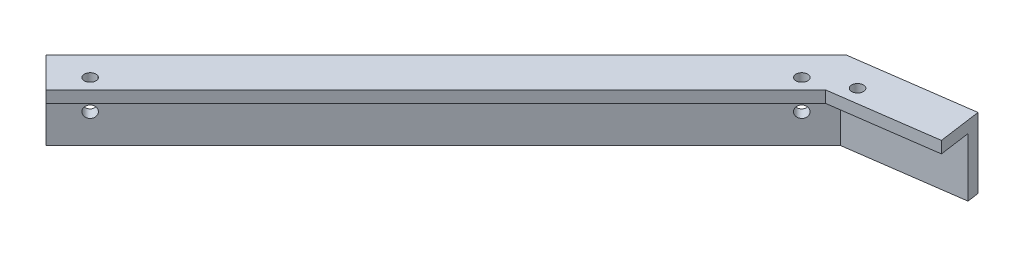
SolidWorks part; units mm, degrees
ref_plane "Alzado" through (0, 0, 0) normal (0, 0, 1) x (1, 0, 0)
ref_plane "Planta" through (0, 0, 0) normal (0, 1, 0) x (1, 0, 0)
ref_plane "Vista lateral" through (0, 0, 0) normal (1, 0, 0) x (0, 0, -1)
sketch "Croquis1" plane through (0, 0, 0) normal (0, 1, 0) x (1, 0, 0)
  line L0 (-35, 0) -> (35, 0) construction
  line L1 (35, 0) -> (65, 0)
  line L2 (65, 0) -> (167.5305, -102.5305)
  line L3 (-35, 0) -> (-65, 0)
  line L4 (-65, 0) -> (-167.5305, -102.5305)
  line L5 (-167.5305, -102.5305) -> (-195, -130) construction
  line L6 (167.5305, -102.5305) -> (195, -130) construction
  line L7 (-167.5305, -102.5305) -> (-161.8736, -108.1873)
  line L8 (167.5305, -102.5305) -> (161.8736, -108.1873)
  line L9 (-161.8736, -108.1873) -> (-61.6863, -8)
  line L10 (-61.6863, -8) -> (-35, -8)
  line L11 (161.8736, -108.1873) -> (61.6863, -8)
  line L12 (61.6863, -8) -> (35, -8)
  line L13 (-35, 0) -> (-35, -8)
  line L14 (35, 0) -> (35, -8)
  line L15 (-65, 0) -> (-62.1716, -2.8284) construction
  line L16 (-62.1716, -2.8284) -> (-67.8284, -8.4853) construction
  line L17 (-67.8284, -8.4853) -> (-159.0452, -99.7021) construction
  line L18 (-159.0452, -99.7021) -> (-164.7021, -105.3589) construction
  line L19 (65, 0) -> (62.1716, -2.8284) construction
  line L20 (62.1716, -2.8284) -> (67.8284, -8.4853) construction
  circle A0 centre (-50, -4) radius 1.5
  circle A1 centre (50, -4) radius 1.5
  circle A2 centre (-67.8284, -8.4853) radius 1.5
  circle A3 centre (-159.0452, -99.7021) radius 1.5
  circle A4 centre (159.0452, -99.7021) radius 1.5
  circle A5 centre (67.8284, -8.4853) radius 1.5
  dimension "D19" = 15
  dimension "D21" = 3
  dimension "D22" = 15
  dimension "D23" = 90
  dimension "D29" = 4
  dimension "D31" = 8
  dimension "D1" = 0
  dimension "D2" = 145
  dimension "D3" = 390
  dimension "D4" = 30
  dimension "D5" = 30
  dimension "D6" = 35
  dimension "D7" = 35
  dimension "D8" = 145
  dimension "D9" = 0
  dimension "D10" = 90
  dimension "D11" = 90
  dimension "D12" = 90
  dimension "D13" = 0
  dimension "D14" = 8
  dimension "D15" = 8
  dimension "D16" = 8
  dimension "D17" = 0
  dimension "D18" = 8
  dimension "D20" = 4
  dimension "D24" = 90
  dimension "D25" = 180
  dimension "D26" = 4
  dimension "D27" = 8
  dimension "D28" = 8
  dimension "D30" = 4
  dimension "D32" = 90
  dimension "D33" = 4
  dimension "D34" = 8
extrude "Saliente-Extruir2" add sketch "Croquis1" along normal blind 3
sketch "Croquis3" plane through (0, 3, 0) normal (0, 1, 0) x (1, 0, 0)
  line L0 (-161.8736, -108.1873) -> (-159.7523, -110.3087)
  line L1 (-159.7523, -110.3087) -> (-60.4437, -11)
  line L2 (-60.4437, -11) -> (-35, -11)
  line L3 (-35, -11) -> (-35, -8)
  line L4 (-167.5305, -102.5305) -> (-161.8736, -108.1873) construction
  line L5 (35, -8) -> (61.6863, -8)
  line L6 (35, -8) -> (35, -11)
  line L7 (35, -11) -> (60.4437, -11)
  line L8 (60.4437, -11) -> (159.7523, -110.3087)
  line L9 (159.7523, -110.3087) -> (161.8736, -108.1873)
  line L10 (61.6863, -8) -> (161.8736, -108.1873) construction
  line L11 (61.6863, -8) -> (161.8736, -108.1873)
  line L12 (-161.8736, -108.1873) -> (-61.6863, -8)
  line L13 (-61.6863, -8) -> (-35, -8)
  dimension "D1" = 3
  dimension "D2" = 180
  dimension "D3" = 90
  dimension "D4" = 3
  dimension "D5" = 90
  dimension "D6" = 90
  dimension "D7" = 3
  dimension "D8" = 3
extrude "Saliente-Extruir3" add sketch "Croquis3" against normal blind 3
sketch "Croquis4" plane through (0, 3, 0) normal (0, 1, 0) x (1, 0, 0)
  line L0 (-67.8284, -8.4853) -> (-65.6364, -10.6773) construction
  line L1 (-65, 0) -> (-167.5305, -102.5305) construction
  line L2 (-156.8532, -101.8941) -> (-159.0452, -99.7021) construction
  line L3 (65.6364, -10.6773) -> (67.8284, -8.4853) construction
  line L4 (167.5305, -102.5305) -> (65, 0) construction
  line L5 (159.0452, -99.7021) -> (156.8532, -101.8941) construction
  circle A0 centre (-50, -7.1) radius 1.5
  circle A1 centre (-50, -4) radius 1.5 construction
  circle A2 centre (-65.6364, -10.6773) radius 1.5
  circle A3 centre (-156.8532, -101.8941) radius 1.5
  circle A4 centre (50, -7.1) radius 1.5
  circle A5 centre (65.6364, -10.6773) radius 1.5
  circle A6 centre (67.8284, -8.4853) radius 1.5 construction
  circle A7 centre (156.8532, -101.8941) radius 1.5
  circle A8 centre (50, -4) radius 1.5 construction
  dimension "D1" = 3.1
  dimension "D2" = 90
  dimension "D4" = 90
  dimension "D6" = 3.1
  dimension "D7" = 90
  dimension "D8" = 90
  dimension "D3" = 3.1
  dimension "D5" = 3.1
  dimension "D9" = 3.1
  dimension "D10" = 3.1
extrude "Cortar-Extruir2" cut sketch "Croquis4" against normal blind 3
sketch "Croquis5" plane through (0, 3, 0) normal (0, 1, 0) x (1, 0, 0)
  circle A0 centre (-159.0452, -99.7021) radius 1.5
  circle A1 centre (-67.8284, -8.4853) radius 1.5
  circle A2 centre (-50, -4) radius 1.5
  circle A3 centre (50, -4) radius 1.5
  circle A4 centre (67.8284, -8.4853) radius 1.5
  circle A5 centre (159.0452, -99.7021) radius 1.5
extrude "Saliente-Extruir4" add sketch "Croquis5" against normal blind 3
sketch "Croquis6" plane through (0, 0, 0) normal (0, -1, 0) x (-1, 0, 0)
  line L0 (167.5305, -102.5305) -> (65, 0)
  line L1 (65, 0) -> (35, 0)
  line L2 (35, 0) -> (65, 0) construction
  line L3 (35, 0) -> (35, -3)
  line L4 (35, -3) -> (63.7574, -3)
  line L5 (63.7574, -3) -> (165.4092, -104.6518)
  line L6 (167.5305, -102.5305) -> (159.7523, -110.3087) construction
  line L7 (165.4092, -104.6518) -> (167.5305, -102.5305)
  line L8 (35, -11) -> (35, 0) construction
  line L9 (-35, 0) -> (-35, -3)
  line L10 (-35, 0) -> (-35, -11) construction
  line L11 (-35, -3) -> (-63.7574, -3)
  line L12 (-63.7574, -3) -> (-165.4092, -104.6518)
  line L13 (-159.7523, -110.3087) -> (-167.5305, -102.5305) construction
  line L14 (-165.4092, -104.6518) -> (-167.5305, -102.5305)
  line L15 (-167.5305, -102.5305) -> (-65, 0)
  line L16 (-65, 0) -> (-35, 0)
  dimension "D1" = 3
  dimension "D2" = 90
  dimension "D3" = 0
  dimension "D4" = 3
  dimension "D5" = 3
  dimension "D6" = 3
extrude "Saliente-Extruir5" add sketch "Croquis6" along normal blind 15
sketch "Croquis7" plane through (0, 0, 0) normal (0, 0, -1) x (-1, 0, 0)
  line L0 (65, -15) -> (35, -15) construction
  circle A0 centre (50, -7.5) radius 1.5
  circle A1 centre (-50, -7.5) radius 1.5
  dimension "D1" = 7.5
extrude "Cortar-Extruir3" cut sketch "Croquis7" against normal blind 15
sketch "Croquis8" plane through (-32.5, 0, -32.5) normal (-0.7071, 0, -0.7071) x (-0.7071, 0, 0.7071)
  line L0 (190.9619, -15) -> (45.9619, -15) construction
  line L1 (190.9619, 3) -> (190.9619, -15) construction
  line L2 (45.9619, 3) -> (45.9619, -15) construction
  line L3 (45.9619, 3) -> (190.9619, 3) construction
  circle A0 centre (182.9619, -7.5) radius 1.5
  circle A1 centre (53.9619, -7.5) radius 1.5
  dimension "D1" = 3
  dimension "D4" = 8
  dimension "D2" = 7.5
  dimension "D3" = 8
  dimension "D5" = 7.5
  dimension "D6" = 10.5
  dimension "D7" = 129
extrude "Cortar-Extruir4" cut sketch "Croquis8" against normal blind 15
sketch "Croquis9" plane through (32.5, 0, -32.5) normal (0.7071, 0, -0.7071) x (-0.7071, 0, -0.7071)
  line L0 (-45.9619, -15) -> (-190.9619, -15) construction
  line L1 (-190.9619, 3) -> (-190.9619, -15) construction
  line L2 (-45.9619, 3) -> (-45.9619, -15) construction
  circle A0 centre (-182.9619, -7.5) radius 1.5
  circle A1 centre (-53.9619, -7.5) radius 1.5
  dimension "D1" = 7.5
  dimension "D3" = 8
  dimension "D2" = 8
extrude "Cortar-Extruir5" cut sketch "Croquis9" against normal blind 15
sketch "Croquis10" plane through (0, 3, 0) normal (0, 1, 0) x (1, 0, 0)
  line L1 (35, 0) -> (206.9557, 0)
  line L2 (35, 0) -> (35, -133.391)
  line L3 (35, -133.391) -> (206.9557, -133.391)
  line L4 (206.9557, 0) -> (206.9557, -133.391)
extrude "Cortar-Extruir7" cut sketch "Croquis10" against normal blind 20
sketch "Croquis11" plane through (0, 3, 0) normal (0, 1, 0) x (1, 0, 0)
  line L0 (-65, 0) -> (-35.2878, 4.1456)
  line L1 (-65, 0) -> (-167.5305, -102.5305) construction
  line L2 (-35.2878, 4.1456) -> (-33.7678, -6.7489)
  line L3 (-33.7678, -6.7489) -> (-59.8287, -10.385)
  line L4 (-60.4437, -11) -> (-59.8287, -10.385)
  line L5 (-159.7523, -110.3087) -> (-60.4437, -11) construction
  line L6 (-65, 0) -> (-60.4437, -11)
  dimension "D1" = 142.943
  dimension "D2" = 30
  dimension "D3" = 11
  dimension "D4" = 90
  dimension "D5" = 180
extrude "Saliente-Extruir6" add sketch "Croquis11" along normal blind 3
sketch "Croquis12" plane through (0, 3, 0) normal (0, 1, 0) x (1, 0, 0)
  line L0 (-60.4437, -11) -> (-59.8287, -10.385)
  line L1 (-59.8287, -10.385) -> (-33.7678, -6.7489)
  line L2 (-33.7678, -6.7489) -> (-35, -11)
  line L3 (-35, -11) -> (-60.4437, -11)
extrude "Cortar-Extruir8" cut sketch "Croquis12" against normal blind 30
sketch "Croquis13" plane through (0, 6, 0) normal (0, 1, 0) x (1, 0, 0)
  line L0 (-65, 0) -> (-60.4437, -11)
  line L1 (-60.4437, -11) -> (-59.8287, -10.385)
  line L2 (-59.8287, -10.385) -> (-33.7678, -6.7489)
  line L3 (-33.7678, -6.7489) -> (-35.2878, 4.1456)
  line L4 (-35.2878, 4.1456) -> (-65, 0)
extrude "Saliente-Extruir8" add sketch "Croquis13" against normal blind 6
sketch "Croquis14" plane through (0, 6, 0) normal (0, 1, 0) x (1, 0, 0)
  line L1 (-21.9705, -18.2623) -> (-79.7331, -18.2623)
  line L2 (-21.9705, -18.2623) -> (-21.9705, 18.4609)
  line L3 (-21.9705, 18.4609) -> (-79.7331, 18.4609)
  line L4 (-79.7331, -18.2623) -> (-79.7331, 18.4609)
extrude "Cortar-Extruir9" cut sketch "Croquis14" against normal blind 3
sketch "Croquis15" plane through (-1.2412, 0, -8.896) normal (-0.1382, 0, -0.9904) x (-0.9904, 0, 0.1382)
  line L0 (64.3764, 3) -> (64.3764, 0) construction
  line L1 (34.3764, 0) -> (64.3764, 0)
  line L2 (34.3764, 0) -> (34.3764, -23.44)
  line L3 (34.3764, -23.44) -> (64.3764, -23.44)
  line L4 (64.3764, 0) -> (64.3764, -23.44)
extrude "Cortar-Extruir11" cut sketch "Croquis15" against normal blind 10
sketch "Croquis16" plane through (0, 0, 0) normal (0, -1, 0) x (-1, 0, 0)
  line L0 (65, 0) -> (35.2878, 4.1456)
  line L1 (35.2878, 4.1456) -> (34.8733, 1.1744)
  line L2 (33.7678, -6.7489) -> (35.2878, 4.1456) construction
  line L3 (34.8733, 1.1744) -> (63.5896, -2.8323)
  line L4 (63.5896, -2.8323) -> (64.4805, -3.7232)
  line L5 (64.4805, -3.7232) -> (65, 0)
  line L6 (64.4805, -3.7232) -> (165.4092, -104.6518) construction
  dimension "D1" = 180
  dimension "D2" = 3
extrude "Saliente-Extruir9" add sketch "Croquis16" along normal blind 15
sketch "Croquis17" plane through (0, 0, 0) normal (0, -1, 0) x (-1, 0, 0)
  line L0 (65, 0) -> (64.0189, -7.0319) construction
  line L1 (65, 0) -> (35.2878, 4.1456) construction
  line L2 (64.0189, -7.0319) -> (56.0956, -5.9264) construction
  line L3 (35.2878, 4.1456) -> (65, 0) construction
  circle A0 centre (56.0956, -5.9264) radius 1.5
  dimension "D1" = 7.1
  dimension "D2" = 90
  dimension "D3" = 90
  dimension "D4" = 8
extrude "Cortar-Extruir12" cut sketch "Croquis17" against normal blind 15
sketch "Sketch1" plane through (-1.2412, 0, -8.896) normal (-0.1382, 0, -0.9904) x (-0.9904, 0, 0.1382)
  line L0 (34.3764, 3) -> (64.3764, 3) construction
  line L2 (64.3764, 3) -> (64.3764, -15) construction
  circle A0 centre (56.3764, -4.1) radius 1.5
  dimension "D1" = 3
  dimension "D2" = 7.1
  dimension "D3" = 8
extrude "Cut-Extrude1" cut sketch "Sketch1" against normal through all
